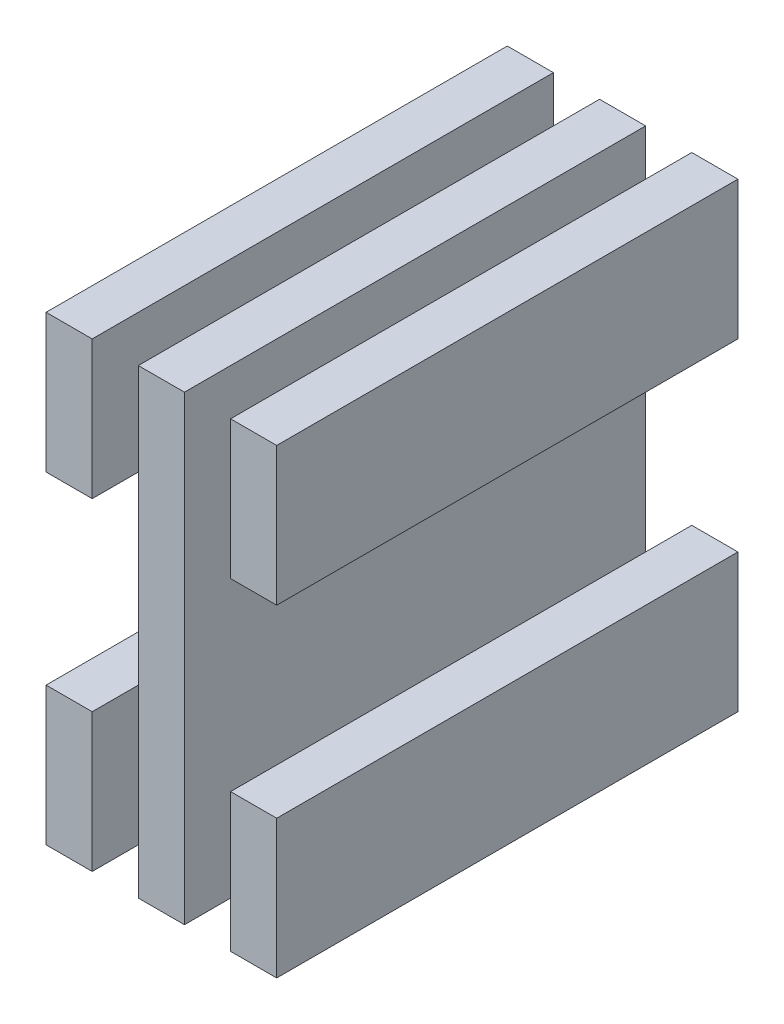
SolidWorks part; units mm, degrees
ref_plane "Front Plane" through (0, 0, 0) normal (0, 0, 1) x (1, 0, 0)
ref_plane "Top Plane" through (0, 0, 0) normal (0, 1, 0) x (1, 0, 0)
ref_plane "Right Plane" through (0, 0, 0) normal (1, 0, 0) x (0, 0, -1)
sketch "Sketch1" plane through (0, 0, 0) normal (0, 1, 0) x (1, 0, 0)
  line L0 (10, 0) -> (10, 50)
  line L1 (0, 0) -> (5, 0)
  line L2 (0, 0) -> (0, 50)
  line L3 (0, 50) -> (5, 50)
  line L4 (5, 0) -> (5, 50)
  line L5 (10, 0) -> (15, 0)
  line L6 (15, 0) -> (15, 50)
  line L7 (10, 50) -> (15, 50)
  line L8 (20, 0) -> (20, 50)
  line L9 (20, 0) -> (25, 0)
  line L10 (25, 0) -> (25, 50)
  line L11 (20, 50) -> (25, 50)
  line L12 (0, 0) -> (10, 0) construction
  dimension "D1" = 5
  dimension "D2" = 50
  dimension "D4" = 10
  dimension "D5" = 5
  dimension "D3" = 3
extrude "Boss-Extrude1" add sketch "Sketch1" along normal blind 50
sketch "Sketch2" plane through (25, 0, 0) normal (1, 0, 0) x (0, 0, -1)
  line L0 (0, 50) -> (0, 0) construction
  line L1 (0, 15) -> (50, 15)
  line L2 (0, 15) -> (0, 35)
  line L3 (0, 35) -> (50, 35)
  line L4 (50, 15) -> (50, 35)
  line L5 (50, 50) -> (50, 0) construction
  line L6 (25, 50) -> (25, 35) construction
  line L7 (0, 50) -> (50, 50) construction
  line L8 (25, 15) -> (25, 0) construction
  line L9 (0, 0) -> (50, 0) construction
  dimension "D1" = 20
extrude "Cut-Extrude1" cut sketch "Sketch2" against normal through all
